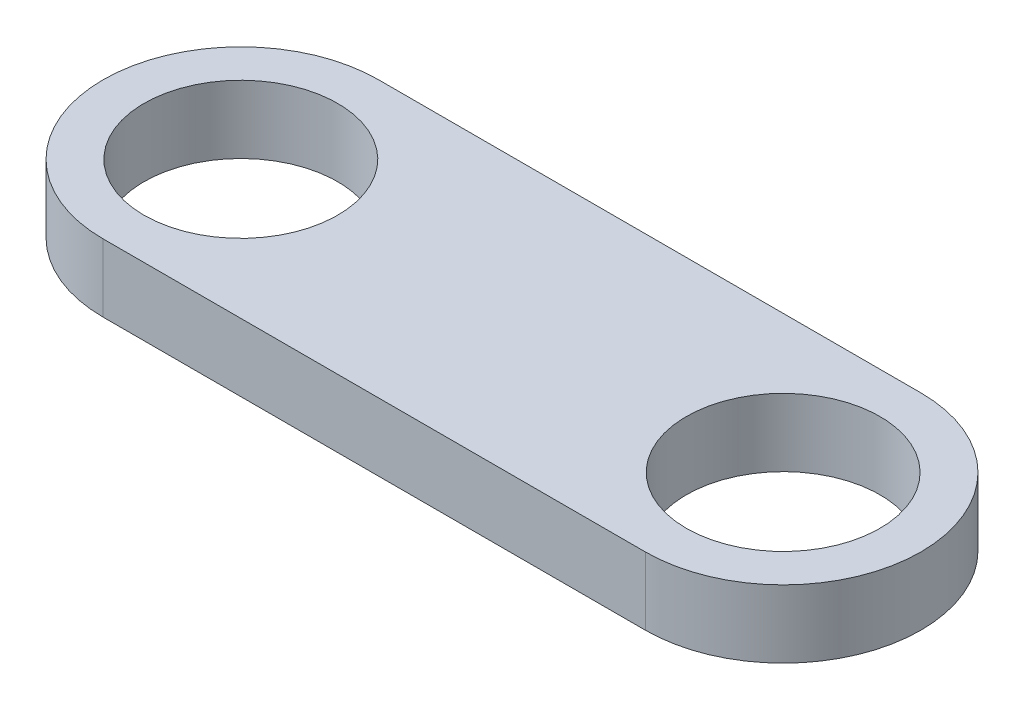
SolidWorks part; units mm, degrees
ref_plane "Front Plane" through (0, 0, 0) normal (0, 0, 1) x (1, 0, 0)
ref_plane "Top Plane" through (0, 0, 0) normal (0, 1, 0) x (1, 0, 0)
ref_plane "Right Plane" through (0, 0, 0) normal (1, 0, 0) x (0, 0, -1)
sketch "Sketch1" plane through (0, 0, 0) normal (0, 1, 0) x (1, 0, 0)
  line L0 (-64, 0) -> (64, 0) construction
  line L1 (-64, 32.5154) -> (64, 32.5154)
  line L2 (-64, -32.5154) -> (64, -32.5154)
  arc A0 (-64, 32.5154) -> (-64, -32.5154) centre (-64, 0) ccw
  arc A1 (64, -32.5154) -> (64, 32.5154) centre (64, 0) ccw
  circle A2 centre (-64, 0) radius 22.8607
  circle A3 centre (64, 0) radius 22.8607
  point P2 (0, 0)
  dimension "D1" = 128
  dimension "28mm" = 45.7214
extrude "Boss-Extrude1" add sketch "Sketch1" along normal blind 16.002
